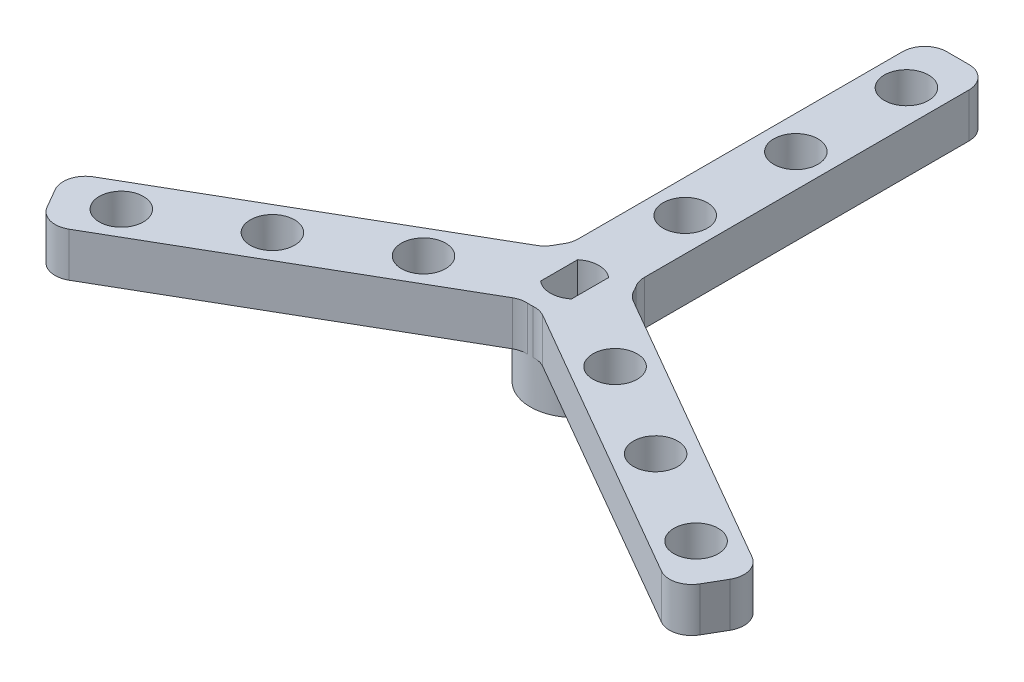
SolidWorks part; units mm, degrees
material "ABS"
ref_plane "Front Plane" through (0, 0, 0) normal (0, 0, 1) x (1, 0, 0)
ref_plane "Top Plane" through (0, 0, 0) normal (0, 1, 0) x (1, 0, 0)
ref_plane "Right Plane" through (0, 0, 0) normal (1, 0, 0) x (0, 0, -1)
sketch "Sketch1" plane through (0, 0, 0) normal (0, 1, 0) x (1, 0, 0)
  line L0 (1.7875, 5.8114) -> (1.7875, 1.6201)
  line L2 (-1.3625, 5.6407) -> (-1.3625, 1.7907)
  line L4 (1.4375, 5.6407) -> (1.4375, 1.7907)
  line L5 (-1.7125, 5.8114) -> (-1.7125, 1.6201)
  arc A1 (-1.3625, 5.6407) -> (1.4375, 5.6407) centre (0.0375, 3.7161) cw
  arc A2 (-1.3625, 1.7907) -> (1.4375, 1.7907) centre (0.0375, 3.7154) ccw
  arc A3 (-1.7125, 5.8114) -> (1.7875, 5.8114) centre (0.0375, 3.7161) cw
  arc A4 (-1.7125, 1.6201) -> (1.7875, 1.6201) centre (0.0375, 3.7154) ccw
  circle A5 centre (0.0375, 3.7154) radius 5
  dimension "D1" = 3.85
  dimension "D3" = 2.38
  dimension "D4" = 2.38
  dimension "D6" = 10
  dimension "D2" = 2.8
  dimension "D5" = 0.35
extrude "Boss-Extrude1" add sketch "Sketch1" along normal blind 10 contours A5 A4 L5 A3 L0
sketch "Sketch2" plane through (0, 10, 0) normal (0, 1, 0) x (1, 0, 0)
  line L0 (0.0375, 47.0226) -> (0.0375, 7.0226) construction
  line L1 (0.0375, 8.7154) -> (0.0375, 9.9323) construction
  line L2 (4.7766, 5.3094) -> (1.0266, -1.1858)
  line L3 (-3.7125, 7.0226) -> (3.7875, 7.0226)
  line L4 (-3.7125, 7.0226) -> (-3.7125, 47.0226)
  line L5 (3.7875, 7.0226) -> (3.7875, 47.0226)
  line L6 (-3.7125, 47.0226) -> (3.7875, 47.0226)
  line L7 (4.7766, 5.3094) -> (39.4176, -14.6906)
  line L8 (1.0266, -1.1858) -> (35.6676, -21.1858)
  line L9 (39.4176, -14.6906) -> (35.6676, -21.1858)
  line L10 (37.5426, -17.9382) -> (2.9016, 2.0618) construction
  line L11 (-4.7016, 5.3094) -> (-0.9516, -1.1858)
  line L12 (-4.7016, 5.3094) -> (-39.3427, -14.6906)
  line L13 (-0.9516, -1.1858) -> (-35.5927, -21.1858)
  line L14 (-39.3427, -14.6906) -> (-35.5927, -21.1858)
  line L15 (-2.8266, 2.0618) -> (-37.4677, -17.9382) construction
  circle A0 centre (0.0375, 3.7154) radius 5 construction
  point P6 (0.0375, 3.7154)
  dimension "D1" = 7.5
  dimension "D2" = 40
  dimension "D3" = 0
  dimension "D4" = 7.5
  dimension "D5" = 40
  dimension "D6" = 120
  dimension "D7" = 7.5
  dimension "D8" = 40
  dimension "D9" = 120
extrude "Boss-Extrude4" add sketch "Sketch2" against normal blind 5
sketch "Sketch4" plane through (0, 10, 0) normal (0, 1, 0) x (1, 0, 0)
  line L0 (3.7875, 7.0226) -> (3.7875, 47.0226) construction
  line L1 (0.0375, 3.7161) -> (37.5426, -17.9382) construction
  line L2 (35.6676, -21.1858) -> (39.4176, -14.6906) construction
  line L3 (0.0375, 3.7161) -> (-37.4677, -17.9382) construction
  line L4 (-39.3427, -14.6906) -> (-35.5927, -21.1858) construction
  circle A0 centre (0.0375, 16.2161) radius 2.5
  circle A1 centre (0.0375, 28.7161) radius 2.5
  circle A2 centre (0.0375, 41.2161) radius 2.5
  circle A3 centre (-10.788, -2.5337) radius 2.5
  circle A4 centre (-21.6135, -8.7834) radius 2.5
  circle A5 centre (-32.439, -15.0331) radius 2.5
  circle A6 centre (10.8629, -2.5337) radius 2.5
  circle A7 centre (21.6884, -8.7834) radius 2.5
  circle A8 centre (32.5139, -15.0331) radius 2.5
  point P5 (0.0375, 3.7161)
  dimension "D1" = 5
  dimension "D2" = 5
  dimension "D7" = 5
  dimension "D3" = 12.5
  dimension "D4" = 12.5
  dimension "D5" = 3.75
  dimension "D6" = 3.75
  dimension "D8" = 3.75
  dimension "D9" = 12.5
extrude "Cut-Extrude1" cut sketch "Sketch4" against normal blind 100
fillet "Fillet1" radius 2.5 6 edges at (4.7766, 7.5, -5.3094) (3.7875, 7.5, -7.0226) (-3.7125, 7.5, -7.0226) (-4.7016, 7.5, -5.3094) (-0.9516, 7.5, 1.1858) (1.0266, 7.5, 1.1858)
fillet "Fillet2" radius 2.5 6 edges at (-3.7125, 7.5, -47.0226) (3.7875, 7.5, -47.0226) (39.4176, 7.5, 14.6906) (35.6676, 7.5, 21.1858) (-39.3427, 7.5, 14.6906) (-35.5927, 7.5, 21.1858)
